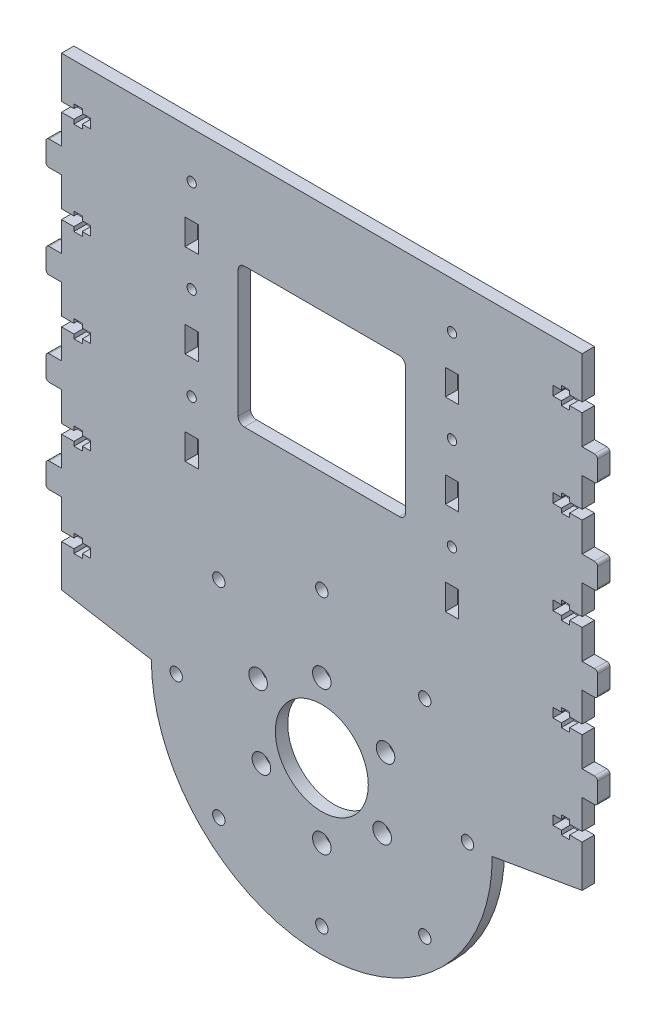
SolidWorks part; units mm, degrees
ref_plane "前视基准面" through (0, 0, 0) normal (0, 0, 1) x (1, 0, 0)
ref_plane "上视基准面" through (0, 0, 0) normal (0, 1, 0) x (1, 0, 0)
ref_plane "右视基准面" through (0, 0, 0) normal (1, 0, 0) x (0, 0, -1)
sketch "草图1" plane through (0, 0, 0) normal (0, 0, 1) x (1, 0, 0)
  line L9 (145, 46.5) -> (149, 46.5)
  line L10 (149, 46.5) -> (149, 45.15)
  line L11 (149, 45.15) -> (151.7, 45.15)
  line L12 (151.7, 45.15) -> (151.7, 46.5)
  line L13 (151.7, 46.5) -> (154.4, 46.5)
  line L14 (154.4, 46.5) -> (154.4, 49.5)
  line L23 (145, 48) -> (143.6922, 48) construction
  line L24 (145, 46.5) -> (145, 49.5) construction
  line L25 (151.7, 50.85) -> (151.7, 49.5)
  line L26 (149, 49.5) -> (149, 50.85)
  line L27 (151.7, 49.5) -> (154.4, 49.5)
  line L28 (149, 50.85) -> (151.7, 50.85)
  line L29 (145, 49.5) -> (149, 49.5)
  line L31 (145, 29) -> (140, 29)
  line L32 (140, 29) -> (140, 37)
  line L33 (140, 37) -> (145, 37)
  line L34 (145, 37) -> (145, 46.5)
  line L35 (141, 33) -> (142.703, 33) construction
  line L43 (149, 15.15) -> (151.7, 15.15)
  line L44 (151.7, 16.5) -> (154.4, 16.5)
  line L45 (149, 16.5) -> (149, 15.15)
  line L69 (145, -97) -> (313, -97) construction
  line L70 (151.7, 15.15) -> (151.7, 16.5)
  line L71 (154.4, 19.5) -> (154.4, 16.5)
  line L72 (151.7, 19.5) -> (154.4, 19.5)
  line L73 (151.7, 20.85) -> (151.7, 19.5)
  line L98 (149, 20.85) -> (151.7, 20.85)
  line L123 (149, 19.5) -> (149, 20.85)
  line L124 (145, 7) -> (145, 16.5)
  line L125 (149, 16.5) -> (145, 16.5)
  line L126 (149, 19.5) -> (145, 19.5)
  line L127 (145, 19.5) -> (145, 29)
  line L128 (154.4, 18) -> (150.6786, 18) construction
  line L129 (141, 3) -> (142.703, 3) construction
  line L130 (140, -1) -> (145, -1)
  line L131 (140, 7) -> (140, -1)
  line L132 (145, 7) -> (140, 7)
  line L133 (145, -1) -> (145, -10.5)
  line L134 (149, -10.5) -> (145, -10.5)
  line L135 (149, -13.5) -> (145, -13.5)
  line L136 (154.4, -12) -> (150.6786, -12) construction
  line L137 (149, -13.5) -> (149, -14.85)
  line L138 (149, -14.85) -> (151.7, -14.85)
  line L139 (151.7, -14.85) -> (151.7, -13.5)
  line L140 (151.7, -13.5) -> (154.4, -13.5)
  line L141 (154.4, -13.5) -> (154.4, -10.5)
  line L142 (151.7, -9.15) -> (151.7, -10.5)
  line L143 (149, -10.5) -> (149, -9.15)
  line L144 (151.7, -10.5) -> (154.4, -10.5)
  line L145 (149, -9.15) -> (151.7, -9.15)
  line L146 (153.6, 108) -> (150.6786, 108) construction
  line L147 (141, 93) -> (142.703, 93) construction
  line L148 (153.6, 78) -> (150.6786, 78) construction
  line L149 (141, 63) -> (142.703, 63) construction
  line L150 (145, 46.5) -> (149, 46.5)
  line L151 (149, 46.5) -> (149, 45.15)
  line L152 (149, 45.15) -> (151.7, 45.15)
  line L153 (151.7, 45.15) -> (151.7, 46.5)
  line L154 (151.7, 46.5) -> (154.4, 46.5)
  line L155 (151.7, 50.85) -> (151.7, 49.5)
  line L156 (149, 49.5) -> (149, 50.85)
  line L157 (151.7, 49.5) -> (154.4, 49.5)
  line L158 (145, 46.5) -> (149, 46.5)
  line L159 (149, 45.15) -> (151.7, 45.15)
  line L160 (151.7, 46.5) -> (154.4, 46.5)
  line L161 (149, 46.5) -> (149, 45.15)
  line L162 (151.7, 45.15) -> (151.7, 46.5)
  line L163 (151.7, 49.5) -> (154.4, 49.5)
  line L164 (151.7, 50.85) -> (151.7, 49.5)
  line L165 (149, 50.85) -> (151.7, 50.85)
  line L166 (149, 49.5) -> (149, 50.85)
  line L167 (145, 49.5) -> (149, 49.5)
  line L168 (149, 50.85) -> (151.7, 50.85)
  line L169 (145, 49.5) -> (149, 49.5)
  line L170 (149, 105.15) -> (151.7, 105.15)
  line L171 (151.7, 106.5) -> (154.4, 106.5)
  line L172 (149, 106.5) -> (149, 105.15)
  line L173 (151.7, 105.15) -> (151.7, 106.5)
  line L174 (154.4, 109.5) -> (154.4, 106.5)
  line L175 (151.7, 109.5) -> (154.4, 109.5)
  line L177 (151.7, 110.85) -> (151.7, 109.5)
  line L178 (149, 110.85) -> (151.7, 110.85)
  line L179 (149, 109.5) -> (149, 110.85)
  line L180 (149, 109.5) -> (145, 109.5)
  line L181 (149, 106.5) -> (145, 106.5)
  line L182 (145, 97) -> (145, 106.5)
  line L183 (145, 89) -> (140, 89)
  line L184 (140, 89) -> (140, 97)
  line L185 (140, 97) -> (145, 97)
  line L186 (145, 76.5) -> (145, 67)
  line L187 (149, 76.5) -> (145, 76.5)
  line L188 (149, 79.5) -> (145, 79.5)
  line L189 (145, 89) -> (145, 79.5)
  line L190 (149, 76.5) -> (149, 75.15)
  line L191 (149, 75.15) -> (151.7, 75.15)
  line L192 (151.7, 75.15) -> (151.7, 76.5)
  line L193 (151.7, 76.5) -> (154.4, 76.5)
  line L194 (154.4, 76.5) -> (154.4, 79.5)
  line L195 (151.7, 80.85) -> (151.7, 79.5)
  line L196 (149, 79.5) -> (149, 80.85)
  line L197 (151.7, 79.5) -> (154.4, 79.5)
  line L198 (149, 80.85) -> (151.7, 80.85)
  line L199 (145, 59) -> (145, 49.5)
  line L200 (140, 59) -> (145, 59)
  line L201 (140, 67) -> (140, 59)
  line L202 (145, 67) -> (140, 67)
  line L203 (145, 46.5) -> (149, 46.5)
  line L204 (149, 45.15) -> (151.7, 45.15)
  line L205 (151.7, 46.5) -> (154.4, 46.5)
  line L206 (149, 46.5) -> (149, 45.15)
  line L207 (151.7, 45.15) -> (151.7, 46.5)
  line L208 (151.7, 49.5) -> (154.4, 49.5)
  line L209 (151.7, 50.85) -> (151.7, 49.5)
  line L210 (149, 50.85) -> (151.7, 50.85)
  line L211 (149, 49.5) -> (149, 50.85)
  line L212 (145, 49.5) -> (149, 49.5)
  line L213 (229, 123) -> (229, -97) construction
  line L214 (306.3, 109.5) -> (306.3, 76.5) construction
  line L215 (309, 109.5) -> (309, 76.5) construction
  line L216 (317, 63) -> (315.297, 63) construction
  line L217 (304.4, 78) -> (307.3214, 78) construction
  line L218 (317, 93) -> (315.297, 93) construction
  line L219 (304.4, 108) -> (307.3214, 108) construction
  line L220 (303.6, -12) -> (307.3214, -12) construction
  line L221 (317, 3) -> (315.297, 3) construction
  line L222 (303.6, 18) -> (307.3214, 18) construction
  line L223 (317, 33) -> (315.297, 33) construction
  line L224 (313, 46.5) -> (313, 49.5) construction
  line L225 (313, 48) -> (314.3078, 48) construction
  line L227 (313, -27) -> (313, -13.5)
  line L228 (313, 123) -> (313, 109.5)
  line L229 (313, -27) -> (313, -97) construction
  line L230 (313, 49.5) -> (309, 49.5)
  line L231 (309, 49.5) -> (309, 50.85)
  line L232 (309, 50.85) -> (306.3, 50.85)
  line L233 (306.3, 50.85) -> (306.3, 49.5)
  line L234 (306.3, 49.5) -> (303.6, 49.5)
  line L235 (306.3, 45.15) -> (306.3, 46.5)
  line L253 (309, 46.5) -> (309, 45.15)
  line L254 (306.3, 46.5) -> (303.6, 46.5)
  line L255 (145, -27) -> (145, -97) construction
  line L256 (309, 45.15) -> (306.3, 45.15)
  line L257 (313, 46.5) -> (309, 46.5)
  line L258 (313, 67) -> (318, 67)
  line L259 (318, 67) -> (318, 59)
  line L260 (318, 59) -> (313, 59)
  line L261 (313, 59) -> (313, 49.5)
  line L262 (309, 80.85) -> (306.3, 80.85)
  line L263 (306.3, 79.5) -> (303.6, 79.5)
  line L264 (309, 79.5) -> (309, 80.85)
  line L265 (306.3, 80.85) -> (306.3, 79.5)
  line L267 (303.6, 76.5) -> (303.6, 79.5)
  line L269 (306.3, 76.5) -> (303.6, 76.5)
  line L270 (306.3, 75.15) -> (306.3, 76.5)
  line L272 (309, 75.15) -> (306.3, 75.15)
  line L273 (309, 76.5) -> (309, 75.15)
  line L274 (313, 89) -> (313, 79.5)
  line L275 (309, 79.5) -> (313, 79.5)
  line L277 (309, 76.5) -> (313, 76.5)
  line L278 (313, 76.5) -> (313, 67)
  line L279 (318, 97) -> (313, 97)
  line L280 (318, 89) -> (318, 97)
  line L281 (313, 89) -> (318, 89)
  line L282 (313, 97) -> (313, 106.5)
  line L283 (309, 106.5) -> (313, 106.5)
  line L284 (309, 109.5) -> (313, 109.5)
  line L285 (309, 109.5) -> (309, 110.85)
  line L286 (309, 110.85) -> (306.3, 110.85)
  line L287 (306.3, 110.85) -> (306.3, 109.5)
  line L288 (306.3, 109.5) -> (303.6, 109.5)
  line L289 (303.6, 109.5) -> (303.6, 106.5)
  line L290 (306.3, 105.15) -> (306.3, 106.5)
  line L291 (309, 106.5) -> (309, 105.15)
  line L292 (306.3, 106.5) -> (303.6, 106.5)
  line L293 (309, 105.15) -> (306.3, 105.15)
  line L294 (313, 49.5) -> (309, 49.5)
  line L296 (309, 50.85) -> (306.3, 50.85)
  line L299 (313, 49.5) -> (309, 49.5)
  line L300 (309, 49.5) -> (309, 50.85)
  line L301 (309, 50.85) -> (306.3, 50.85)
  line L302 (306.3, 50.85) -> (306.3, 49.5)
  line L303 (306.3, 49.5) -> (303.6, 49.5)
  line L304 (306.3, 45.15) -> (306.3, 46.5)
  line L305 (309, 46.5) -> (309, 45.15)
  line L306 (306.3, 46.5) -> (303.6, 46.5)
  line L307 (309, 45.15) -> (306.3, 45.15)
  line L308 (313, 46.5) -> (309, 46.5)
  line L309 (306.3, 49.5) -> (303.6, 49.5)
  line L310 (309, 49.5) -> (309, 50.85)
  line L312 (306.3, 50.85) -> (306.3, 49.5)
  line L314 (306.3, 46.5) -> (303.6, 46.5)
  line L315 (306.3, 45.15) -> (306.3, 46.5)
  line L317 (309, 45.15) -> (306.3, 45.15)
  line L320 (309, 46.5) -> (309, 45.15)
  line L321 (313, 46.5) -> (309, 46.5)
  line L322 (309, -9.15) -> (306.3, -9.15)
  line L323 (306.3, -10.5) -> (303.6, -10.5)
  line L324 (309, -10.5) -> (309, -9.15)
  line L325 (306.3, -9.15) -> (306.3, -10.5)
  line L326 (303.6, -13.5) -> (303.6, -10.5)
  line L327 (306.3, -13.5) -> (303.6, -13.5)
  line L328 (306.3, -14.85) -> (306.3, -13.5)
  line L329 (309, -14.85) -> (306.3, -14.85)
  line L330 (309, -13.5) -> (309, -14.85)
  line L331 (309, -13.5) -> (313, -13.5)
  line L332 (309, -10.5) -> (313, -10.5)
  line L333 (313, -1) -> (313, -10.5)
  line L334 (313, 7) -> (318, 7)
  line L335 (318, 7) -> (318, -1)
  line L336 (318, -1) -> (313, -1)
  line L337 (313, 19.5) -> (313, 29)
  line L338 (309, 19.5) -> (313, 19.5)
  line L339 (309, 16.5) -> (313, 16.5)
  line L340 (313, 7) -> (313, 16.5)
  line L341 (309, 19.5) -> (309, 20.85)
  line L342 (309, 20.85) -> (306.3, 20.85)
  line L343 (306.3, 20.85) -> (306.3, 19.5)
  line L344 (306.3, 19.5) -> (303.6, 19.5)
  line L345 (303.6, 19.5) -> (303.6, 16.5)
  line L346 (306.3, 15.15) -> (306.3, 16.5)
  line L347 (309, 16.5) -> (309, 15.15)
  line L348 (306.3, 16.5) -> (303.6, 16.5)
  line L349 (309, 15.15) -> (306.3, 15.15)
  line L350 (313, 37) -> (313, 46.5)
  line L352 (318, 37) -> (313, 37)
  line L353 (318, 29) -> (318, 37)
  line L355 (313, 29) -> (318, 29)
  line L356 (313, 49.5) -> (309, 49.5)
  line L357 (309, 50.85) -> (306.3, 50.85)
  line L358 (306.3, 49.5) -> (303.6, 49.5)
  line L359 (309, 49.5) -> (309, 50.85)
  line L360 (306.3, 50.85) -> (306.3, 49.5)
  line L361 (303.6, 46.5) -> (303.6, 49.5)
  line L362 (145, 123) -> (313, 123)
  line L363 (306.3, 46.5) -> (303.6, 46.5)
  line L364 (306.3, 45.15) -> (306.3, 46.5)
  line L365 (149, 109.5) -> (149, 76.5) construction
  line L366 (151.7, 109.5) -> (151.7, 76.5) construction
  line L367 (309, 45.15) -> (306.3, 45.15)
  line L369 (187, 108) -> (187, 48) construction
  line L370 (184.85, 97.15) -> (189.15, 97.15)
  line L371 (184.85, 97.15) -> (184.85, 88.85)
  line L372 (184.85, 88.85) -> (189.15, 88.85)
  line L373 (189.15, 97.15) -> (189.15, 88.85)
  line L374 (184.85, 97.15) -> (189.15, 88.85) construction
  line L375 (184.85, 88.85) -> (189.15, 97.15) construction
  line L386 (309, 46.5) -> (309, 45.15)
  line L387 (313, 46.5) -> (309, 46.5)
  line L389 (273.15, 58.85) -> (268.85, 67.15) construction
  line L391 (273.15, 67.15) -> (268.85, 58.85) construction
  line L392 (273.15, 88.85) -> (268.85, 97.15) construction
  line L420 (229, -32) -> (229, 123) construction
  line L421 (229, -32) -> (245.7973, -32) construction
  line L422 (229, -32) -> (253.7224, -46.2735) construction
  line L423 (184.85, 67.15) -> (189.15, 67.15)
  line L424 (184.85, 67.15) -> (184.85, 58.85)
  line L425 (184.85, 58.85) -> (189.15, 58.85)
  line L426 (189.15, 67.15) -> (189.15, 58.85)
  line L427 (184.85, 67.15) -> (189.15, 58.85) construction
  line L432 (184.85, 58.85) -> (189.15, 67.15) construction
  line L433 (273.15, 97.15) -> (268.85, 88.85) construction
  line L434 (271, 108) -> (271, 48) construction
  line L435 (268.85, 67.15) -> (268.85, 58.85)
  line L436 (273.15, 58.85) -> (268.85, 58.85)
  line L437 (273.15, 67.15) -> (273.15, 58.85)
  line L438 (273.15, 67.15) -> (268.85, 67.15)
  line L439 (268.85, 97.15) -> (268.85, 88.85)
  line L440 (273.15, 88.85) -> (268.85, 88.85)
  line L441 (273.15, 97.15) -> (273.15, 88.85)
  line L442 (273.15, 97.15) -> (268.85, 97.15)
  line L443 (187, 48) -> (187, 33) construction
  line L444 (273.15, 28.85) -> (268.85, 37.15) construction
  line L445 (184.85, 37.15) -> (189.15, 37.15)
  line L446 (184.85, 37.15) -> (184.85, 28.85)
  line L447 (184.85, 28.85) -> (189.15, 28.85)
  line L448 (189.15, 37.15) -> (189.15, 28.85)
  line L449 (184.85, 37.15) -> (189.15, 28.85) construction
  line L450 (184.85, 28.85) -> (189.15, 37.15) construction
  line L451 (273.15, 37.15) -> (268.85, 28.85) construction
  line L452 (271, 48) -> (271, 33) construction
  line L454 (268.85, 37.15) -> (268.85, 28.85)
  line L456 (273.15, 28.85) -> (268.85, 28.85)
  line L457 (273.15, 37.15) -> (273.15, 28.85)
  line L458 (273.15, 37.15) -> (268.85, 37.15)
  line L462 (174, -32) -> (145, -27)
  line L463 (284, -32) -> (313, -27)
  line L464 (187, 108) -> (271, 108) construction
  line L465 (187, 33) -> (271, 33) construction
  line L466 (202, 93) -> (256, 93)
  line L467 (256, 93) -> (256, 48)
  line L468 (256, 48) -> (256, 48)
  line L469 (202, 48) -> (256, 48)
  line L470 (202, 48) -> (202, 48)
  line L471 (202, 93) -> (202, 48)
  line L592 (145, 123) -> (145, 109.5)
  line L594 (145, -27) -> (145, -13.5)
  circle A88 centre (187, 108) radius 1.5
  circle A97 centre (229, -32) radius 23.75 construction
  circle A98 centre (229, -32) radius 22.5 construction
  circle A99 centre (229, -55.75) radius 3
  circle A100 centre (248.4856, -43.25) radius 3
  circle A101 centre (229, -32) radius 15
  circle A102 centre (276, -32) radius 2
  circle A103 centre (208.4319, -20.125) radius 3
  circle A104 centre (249.5681, -20.125) radius 3
  circle A105 centre (209.5144, -43.25) radius 3
  circle A106 centre (229, -9.5) radius 3
  circle A114 centre (187, 78) radius 1.5
  circle A115 centre (187, 48) radius 1.5
  circle A116 centre (271, 48) radius 1.5
  circle A117 centre (271, 78) radius 1.5
  circle A118 centre (271, 108) radius 1.5
  circle A119 centre (262.234, -65.234) radius 2
  circle A120 centre (229, -79) radius 2
  circle A121 centre (195.766, -65.234) radius 2
  circle A122 centre (182, -32) radius 2
  circle A123 centre (195.766, 1.234) radius 2
  circle A124 centre (229, 15) radius 2
  circle A125 centre (262.234, 1.234) radius 2
  circle A126 centre (229, -32) radius 55 construction
  arc A127 (174, -32) -> (284, -32) centre (229, -32) ccw
  point P15 (144.3461, 48)
  point P199 (187, 93)
  point P208 (187, 63)
  point P227 (271, 63)
  point P228 (271, 93)
  dimension "D2" = 15
  dimension "D7" = 8
  dimension "D1" = 2.7
  dimension "D9" = 15
  dimension "D10" = 4
  dimension "D11" = 4.3
  dimension "D13" = 15
  dimension "D14" = 42
  dimension "D15" = 47.5
  dimension "D16" = 45
  dimension "D17" = 6
  dimension "D19" = 6
  dimension "D21" = 4
  dimension "D22" = 3
  dimension "D3" = 4
  dimension "D4" = 2.7
  dimension "D5" = 2.7
  dimension "D6" = 1.35
  dimension "D8" = 1.5
  dimension "D12" = 8.3
  dimension "D18" = 30
  dimension "D20" = 47
  dimension "D23" = 15
  dimension "D24" = 8
extrude "凸台-拉伸1" add sketch "草图1" along normal blind 4
sketch "草图8" plane through (145, 0, 0) normal (-1, 0, 0) x (0, 0, 1)
  line L0 (2, 109.5) -> (2, 106.5)
  line L1 (4, 109.5) -> (0, 109.5) construction
  line L2 (4, 106.5) -> (0, 106.5) construction
  circle A0 centre (2, 108) radius 1.5
fillet "圆角1" radius 1 16 edges at (140, 97, 2) (140, 89, 2) (318, 97, 2) (318, 67, 2) (318, 7, 2) (318, -1, 2) (318, 37, 2) (318, 29, 2) (318, 59, 2) (318, 89, 2) (140, 67, 2) (140, 59, 2) (140, 37, 2) (140, 29, 2) (140, 7, 2) (140, -1, 2)
fillet "圆角2" radius 2 4 edges at (256, 48, 2) (256, 93, 2) (202, 48, 2) (202, 93, 2)
